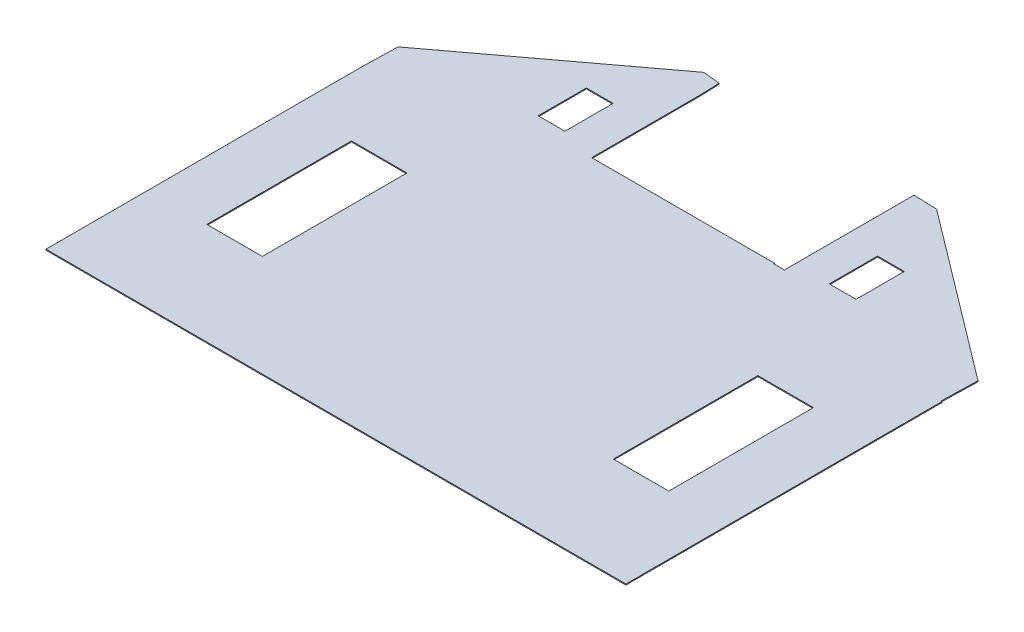
SolidWorks part; units mm, degrees
ref_plane "Front Plane" through (0, 0, 0) normal (0, 0, 1) x (1, 0, 0)
ref_plane "Top Plane" through (0, 0, 0) normal (0, 1, 0) x (1, 0, 0)
ref_plane "Right Plane" through (0, 0, 0) normal (1, 0, 0) x (0, 0, -1)
sketch "Sketch1" plane through (0, 0, 0) normal (0, 1, 0) x (1, 0, 0)
  line L1 (-292.25, 307.9183) -> (-292.25, -10.9917)
  line L2 (-292.25, -10.9917) -> (292.25, -10.9917)
  line L3 (292.25, -10.9917) -> (292.25, 307.9183)
  line L4 (292.25, 307.9183) -> (0, 531.4036)
  line L5 (0, 531.4036) -> (-292.25, 307.9183)
  line L6 (113.6299, 475.2644) -> (293.15, 337.9843) construction
  point P1 (0, -10.9917)
  dimension "D1" = 584.5
  dimension "D2" = 318.91
extrude "Boss-Extrude1" add sketch "Sketch1" along normal blind 1
sketch "Sketch3" plane through (0, 1, 0) normal (0, 1, 0) x (1, 0, 0)
  line L0 (-179.6882, 66.8345) -> (-179.6882, 262.8345) construction
  line L1 (-232.6882, 237.8345) -> (-176.6882, 237.8345)
  line L2 (-232.6882, 237.8345) -> (-232.6882, 91.8345)
  line L3 (-232.6882, 91.8345) -> (-176.6882, 91.8345)
  line L4 (-176.6882, 237.8345) -> (-176.6882, 91.8345)
  line L5 (-229.6882, 262.8345) -> (-229.6882, 66.8345) construction
  line L6 (0, 0) -> (0, 166.0645) construction
  line L11 (230.5882, 66.8345) -> (230.5882, 262.8345) construction
  line L12 (177.5882, 237.8345) -> (233.5882, 237.8345)
  line L13 (177.5882, 237.8345) -> (177.5882, 91.8345)
  line L14 (177.5882, 91.8345) -> (233.5882, 91.8345)
  line L15 (233.5882, 237.8345) -> (233.5882, 91.8345)
  line L16 (180.5882, 262.8345) -> (180.5882, 66.8345) construction
  line L17 (180.5882, 66.8345) -> (230.5882, 66.8345) construction
  line L18 (230.5882, 262.8345) -> (180.5882, 262.8345) construction
  dimension "D1" = 3
  dimension "D2" = 3
  dimension "D3" = 3
  dimension "D4" = 3
  dimension "D5" = 25
  dimension "D6" = 25
extrude "Cut-Extrude2" cut sketch "Sketch3" against normal blind 10
sketch "Sketch4" plane through (0, 1, 0) normal (0, 1, 0) x (1, 0, 0)
  line L1 (140.7121, 474.4083) -> (-182.8142, 474.4083)
  line L2 (140.7121, 474.4083) -> (140.7121, 548.1932)
  line L3 (140.7121, 548.1932) -> (-182.8142, 548.1932)
  line L4 (-182.8142, 474.4083) -> (-182.8142, 548.1932)
  line L5 (140.7121, 474.4083) -> (-182.8142, 548.1932) construction
  line L6 (140.7121, 548.1932) -> (-182.8142, 474.4083) construction
  point P0 (-21.051, 511.3007)
extrude "Cut-Extrude4" cut sketch "Sketch4" against normal through all both
sketch "Sketch5" plane through (0, 1, 0) normal (0, 1, 0) x (1, 0, 0)
  line L1 (292.25, 307.9183) -> (293.15, 307.9183)
  line L2 (292.25, 307.9183) -> (292.25, -10.9917)
  line L3 (292.25, -10.9917) -> (293.15, -10.9917)
  line L4 (293.15, 307.9183) -> (293.15, -10.9917)
extrude "Boss-Extrude2" add sketch "Sketch5" against normal up to surface (1 mm away) up to face at (0, 0, -257.1116)
sketch "Sketch6" plane through (0, 1, 0) normal (0, 1, 0) x (1, 0, 0)
  line L1 (87.75, 454.4481) -> (-96.85, 454.4481)
  line L2 (87.75, 454.4481) -> (87.75, 344.4083)
  line L3 (87.75, 344.4083) -> (-96.85, 344.4083)
  line L4 (-96.85, 454.4481) -> (-96.85, 344.4083)
extrude "Cut-Extrude6" cut sketch "Sketch6" against normal blind 11.5 and the other way through all
sketch "Sketch7" plane through (0, 1, 0) normal (0, 1, 0) x (1, 0, 0)
  line L0 (-136.4456, 351.979) -> (-136.4456, 404.979) construction
  line L1 (-160.4456, 402.7258) -> (-133.4456, 402.7258)
  line L2 (-160.4456, 402.7258) -> (-160.4456, 354.0128)
  line L3 (-160.4456, 354.0128) -> (-133.4456, 354.0128)
  line L4 (-133.4456, 402.7258) -> (-133.4456, 354.0128)
  line L5 (-157.4456, 404.979) -> (-157.4456, 351.979) construction
  line L6 (0, 0) -> (0, 630.4306) construction
  line L7 (160.4456, 354.0128) -> (133.4456, 354.0128)
  line L8 (133.4456, 402.7258) -> (133.4456, 354.0128)
  line L9 (160.4456, 402.7258) -> (133.4456, 402.7258)
  line L10 (160.4456, 402.7258) -> (160.4456, 354.0128)
  dimension "D1" = 3
  dimension "D2" = 3
extrude "Cut-Extrude7" cut sketch "Sketch7" against normal through all both and the other way through all
sketch "Sketch8" plane through (0, 1, 0) normal (0, 1, 0) x (1, 0, 0)
  line L1 (-114.4278, 494.5886) -> (153.7571, 494.5886)
  line L2 (-114.4278, 494.5886) -> (-114.4278, 453.5967)
  line L3 (-114.4278, 453.5967) -> (153.7571, 453.5967)
  line L4 (153.7571, 494.5886) -> (153.7571, 453.5967)
extrude "Cut-Extrude8" cut sketch "Sketch8" against normal through all both
sketch "Sketch9" plane through (0, 1, 0) normal (0, 1, 0) x (1, 0, 0)
  line L0 (-292.25, 307.9183) -> (-291.361, 343.5193)
  line L1 (-291.361, 343.5193) -> (-114.7605, 475.5998)
  line L2 (-114.7605, 475.5998) -> (-97.5902, 473.7561)
  line L3 (-97.5902, 473.7561) -> (-96.85, 453.5967)
  line L4 (-96.85, 453.5967) -> (-101.7475, 453.5967)
  line L5 (-101.7475, 453.5967) -> (-292.25, 307.9183)
  line L6 (87.75, 453.5967) -> (87.75, 474.6779)
  line L7 (87.75, 474.6779) -> (122.261, 473.5193)
  line L8 (122.261, 473.5193) -> (293.15, 344.4083)
  line L9 (293.15, 344.4083) -> (292.25, 307.9183)
  line L10 (292.25, 307.9183) -> (101.7475, 453.5967)
  line L11 (101.7475, 453.5967) -> (87.75, 453.5967)
  point P19 (0, 0)
  point P24 (0, 0)
extrude "Boss-Extrude3" add sketch "Sketch9" against normal blind 1
sketch "Sketch10" plane through (0, 1, 0) normal (0, 1, 0) x (1, 0, 0)
  line L0 (87.75, 474.6779) -> (98.639, 474.4083)
  line L1 (98.639, 474.4083) -> (98.639, 343.5193)
  line L2 (98.639, 343.5193) -> (87.75, 343.5193)
  line L3 (87.75, 343.5193) -> (87.75, 474.6779)
  line L5 (98.639, 343.5193) -> (-97.739, 343.5193) construction
  point P4 (0, 0)
  point P9 (0, 0)
  point P16 (0, 0)
  point P17 (98.639, 474.4083)
  point P20 (0, 0)
  point P21 (87.75, 343.5193)
  point P24 (0, 0)
extrude "Cut-Extrude9" cut sketch "Sketch10" against normal through all both and the other way through all
